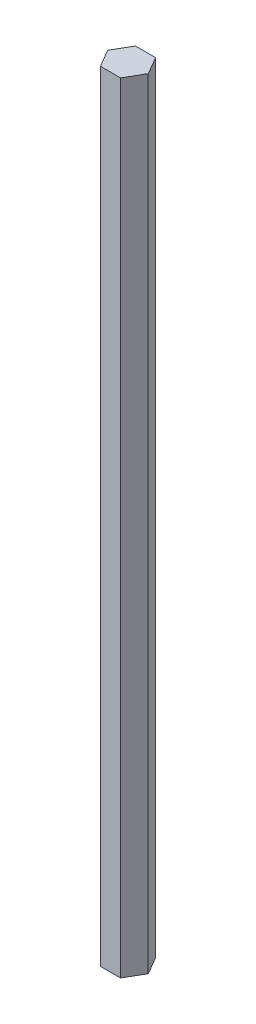
SolidWorks part; units mm, degrees
ref_plane "Front Plane" through (0, 0, 0) normal (0, 0, 1) x (1, 0, 0)
ref_plane "Top Plane" through (0, 0, 0) normal (0, 1, 0) x (1, 0, 0)
ref_plane "Right Plane" through (0, 0, 0) normal (1, 0, 0) x (0, 0, -1)
sketch "Sketch1" plane through (0, 0, 0) normal (0, 1, 0) x (1, 0, 0)
  line L1 (1.7321, 0) -> (0.866, 1.5)
  line L2 (0.866, 1.5) -> (-0.866, 1.5)
  line L3 (-0.866, 1.5) -> (-1.7321, 0)
  line L4 (-1.7321, 0) -> (-0.866, -1.5)
  line L5 (-0.866, -1.5) -> (0.866, -1.5)
  line L6 (0.866, -1.5) -> (1.7321, 0)
  circle A0 centre (0, 0) radius 1.5 construction
  dimension "D1" = 3
extrude "Boss-Extrude1" add sketch "Sketch1" along normal up to surface (5.452 mm away) and the other way offset from surface (61.3 mm away) 20.5
